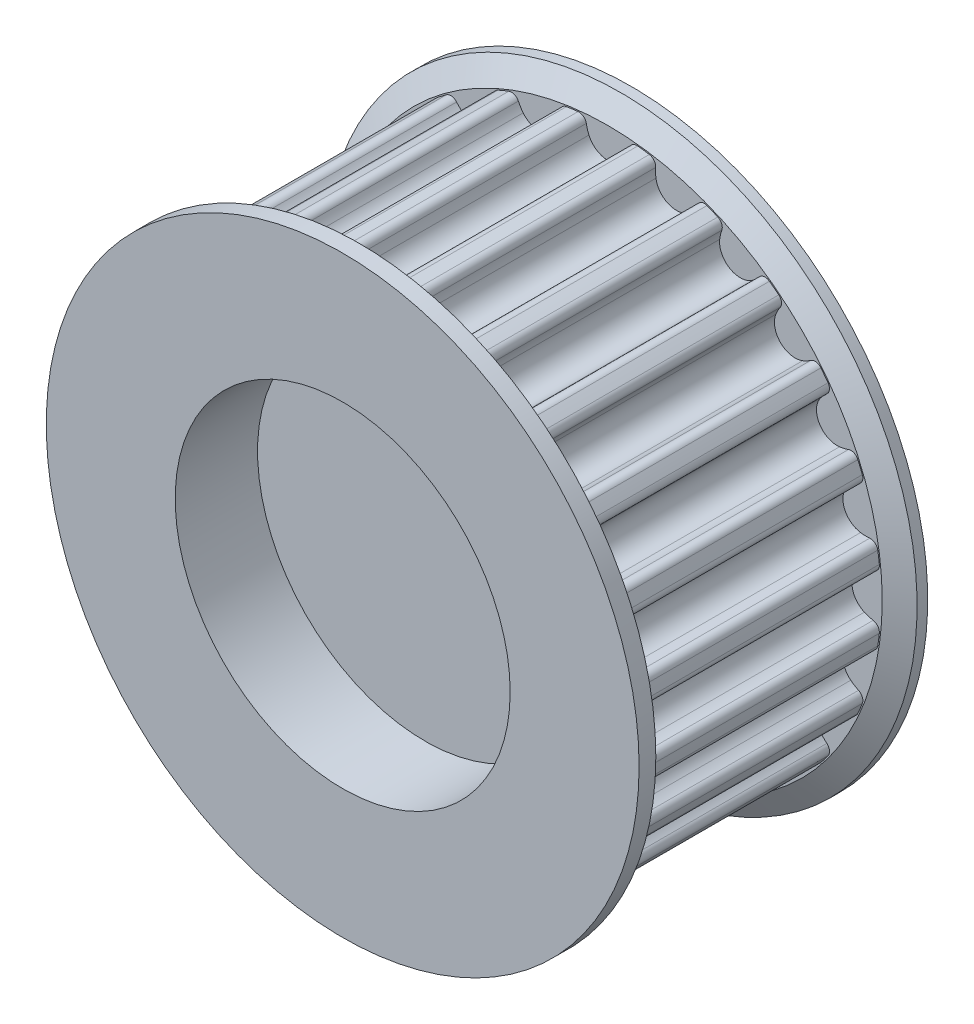
SolidWorks part; units mm, degrees
material "ABS"
ref_plane "Front" through (0, 0, 0) normal (0, 0, 1) x (1, 0, 0)
ref_plane "Top" through (0, 0, 0) normal (0, 1, 0) x (1, 0, 0)
ref_plane "Right" through (0, 0, 0) normal (1, 0, 0) x (0, 0, -1)
sketch "Sketch1" plane through (0, 0, 0) normal (0, 0, 1) x (1, 0, 0)
  arc A0 (-1.2885, 17.4069) -> (-1.4679, 18.0028) centre (1.1557, 18.4677) cw
  arc A1 (-1.4679, 18.0028) -> (-2.0236, 18.4192) centre (-1.9681, 17.9142) ccw
  arc A2 (-2.0236, 18.4192) -> (-2.8126, 18.3153) centre (0, 0) ccw
  arc A3 (-2.8126, 18.3153) -> (-3.2416, 17.7693) centre (-2.7355, 17.8132) ccw
  arc A4 (-3.2416, 17.7693) -> (-3.2606, 17.1473) centre (-5.8961, 17.5393) cw
  arc A5 (-3.2606, 17.1473) -> (-5.7499, 16.4803) centre (-4.65, 17.3539) cw
  arc A6 (-5.7499, 16.4803) -> (-6.0774, 17.0095) centre (-3.6635, 18.1375) cw
  arc A7 (-6.0774, 17.0095) -> (-6.7219, 17.2678) centre (-6.5376, 16.7944) ccw
  arc A8 (-6.7219, 17.2678) -> (-7.4571, 16.9633) centre (0, 0) ccw
  arc A9 (-7.4571, 16.9633) -> (-7.7302, 16.3249) centre (-7.2527, 16.4982) ccw
  arc A10 (-7.7302, 16.3249) -> (-7.5876, 15.7191) centre (-10.2347, 15.4156) cw
  arc A11 (-7.5876, 15.7191) -> (-9.8193, 14.4306) centre (-8.9831, 15.5591) cw
  arc A12 (-9.8193, 14.4306) -> (-10.2727, 14.857) centre (-8.233, 16.5713) cw
  arc A13 (-10.2727, 14.857) -> (-10.9621, 14.9397) centre (-10.6615, 14.5301) ccw
  arc A14 (-10.9621, 14.9397) -> (-11.5934, 14.4552) centre (0, 0) ccw
  arc A15 (-11.5934, 14.4552) -> (-11.692, 13.7679) centre (-11.2756, 14.0589) ccw
  arc A16 (-11.692, 13.7679) -> (-11.3974, 13.2197) centre (-13.8758, 12.2414) cw
  arc A17 (-11.3974, 13.2197) -> (-13.2197, 11.3974) centre (-12.704, 12.704) cw
  arc A18 (-13.2197, 11.3974) -> (-13.7679, 11.692) centre (-12.2414, 13.8758) cw
  arc A19 (-13.7679, 11.692) -> (-14.4552, 11.5934) centre (-14.0589, 11.2756) ccw
  arc A20 (-14.4552, 11.5934) -> (-14.9397, 10.9621) centre (0, 0) ccw
  arc A21 (-14.9397, 10.9621) -> (-14.857, 10.2727) centre (-14.5301, 10.6615) ccw
  arc A22 (-14.857, 10.2727) -> (-14.4306, 9.8193) centre (-16.5713, 8.233) cw
  arc A23 (-14.4306, 9.8193) -> (-15.7191, 7.5876) centre (-15.5591, 8.9831) cw
  arc A24 (-15.7191, 7.5876) -> (-16.3249, 7.7302) centre (-15.4156, 10.2347) cw
  arc A25 (-16.3249, 7.7302) -> (-16.9633, 7.4571) centre (-16.4982, 7.2527) ccw
  arc A26 (-16.9633, 7.4571) -> (-17.2678, 6.7219) centre (0, 0) ccw
  arc A27 (-17.2678, 6.7219) -> (-17.0095, 6.0774) centre (-16.7944, 6.5376) ccw
  arc A28 (-17.0095, 6.0774) -> (-16.4803, 5.7499) centre (-18.1375, 3.6635) cw
  arc A29 (-16.4803, 5.7499) -> (-17.1473, 3.2606) centre (-17.3539, 4.65) cw
  arc A30 (-17.1473, 3.2606) -> (-17.7693, 3.2416) centre (-17.5393, 5.8961) cw
  arc A31 (-17.7693, 3.2416) -> (-18.3153, 2.8126) centre (-17.8132, 2.7355) ccw
  arc A32 (-18.3153, 2.8126) -> (-18.4192, 2.0236) centre (0, 0) ccw
  arc A33 (-18.4192, 2.0236) -> (-18.0028, 1.4679) centre (-17.9142, 1.9681) ccw
  arc A34 (-18.0028, 1.4679) -> (-17.4069, 1.2885) centre (-18.4677, -1.1557) cw
  arc A35 (-17.4069, 1.2885) -> (-17.4069, -1.2885) centre (-17.9661, 0) cw
  arc A36 (-17.4069, -1.2885) -> (-18.0028, -1.4679) centre (-18.4677, 1.1557) cw
  arc A37 (-18.0028, -1.4679) -> (-18.4192, -2.0236) centre (-17.9142, -1.9681) ccw
  arc A38 (-18.4192, -2.0236) -> (-18.3153, -2.8126) centre (0, 0) ccw
  arc A39 (-18.3153, -2.8126) -> (-17.7693, -3.2416) centre (-17.8132, -2.7355) ccw
  arc A40 (-17.7693, -3.2416) -> (-17.1473, -3.2606) centre (-17.5393, -5.8961) cw
  arc A41 (-17.1473, -3.2606) -> (-16.4803, -5.7499) centre (-17.3539, -4.65) cw
  arc A42 (-16.4803, -5.7499) -> (-17.0095, -6.0774) centre (-18.1375, -3.6635) cw
  arc A43 (-17.0095, -6.0774) -> (-17.2678, -6.7219) centre (-16.7944, -6.5376) ccw
  arc A44 (-17.2678, -6.7219) -> (-16.9633, -7.4571) centre (0, 0) ccw
  arc A45 (-16.9633, -7.4571) -> (-16.3249, -7.7302) centre (-16.4982, -7.2527) ccw
  arc A46 (-16.3249, -7.7302) -> (-15.7191, -7.5876) centre (-15.4156, -10.2347) cw
  arc A47 (-15.7191, -7.5876) -> (-14.4306, -9.8193) centre (-15.5591, -8.9831) cw
  arc A48 (-14.4306, -9.8193) -> (-14.857, -10.2727) centre (-16.5713, -8.233) cw
  arc A49 (-14.857, -10.2727) -> (-14.9397, -10.9621) centre (-14.5301, -10.6615) ccw
  arc A50 (-14.9397, -10.9621) -> (-14.4552, -11.5934) centre (0, 0) ccw
  arc A51 (-14.4552, -11.5934) -> (-13.7679, -11.692) centre (-14.0589, -11.2756) ccw
  arc A52 (-13.7679, -11.692) -> (-13.2197, -11.3974) centre (-12.2414, -13.8758) cw
  arc A53 (-13.2197, -11.3974) -> (-11.3974, -13.2197) centre (-12.704, -12.704) cw
  arc A54 (-11.3974, -13.2197) -> (-11.692, -13.7679) centre (-13.8758, -12.2414) cw
  arc A55 (-11.692, -13.7679) -> (-11.5934, -14.4552) centre (-11.2756, -14.0589) ccw
  arc A56 (-11.5934, -14.4552) -> (-10.9621, -14.9397) centre (0, 0) ccw
  arc A57 (-10.9621, -14.9397) -> (-10.2727, -14.857) centre (-10.6615, -14.5301) ccw
  arc A58 (-10.2727, -14.857) -> (-9.8193, -14.4306) centre (-8.233, -16.5713) cw
  arc A59 (-9.8193, -14.4306) -> (-7.5876, -15.7191) centre (-8.9831, -15.5591) cw
  arc A60 (-7.5876, -15.7191) -> (-7.7302, -16.3249) centre (-10.2347, -15.4156) cw
  arc A61 (-7.7302, -16.3249) -> (-7.4571, -16.9633) centre (-7.2527, -16.4982) ccw
  arc A62 (-7.4571, -16.9633) -> (-6.7219, -17.2678) centre (0, 0) ccw
  arc A63 (-6.7219, -17.2678) -> (-6.0774, -17.0095) centre (-6.5376, -16.7944) ccw
  arc A64 (-6.0774, -17.0095) -> (-5.7499, -16.4803) centre (-3.6635, -18.1375) cw
  arc A65 (-5.7499, -16.4803) -> (-3.2606, -17.1473) centre (-4.65, -17.3539) cw
  arc A66 (-3.2606, -17.1473) -> (-3.2416, -17.7693) centre (-5.8961, -17.5393) cw
  arc A67 (-3.2416, -17.7693) -> (-2.8126, -18.3153) centre (-2.7355, -17.8132) ccw
  arc A68 (-2.8126, -18.3153) -> (-2.0236, -18.4192) centre (0, 0) ccw
  arc A69 (-2.0236, -18.4192) -> (-1.4679, -18.0028) centre (-1.9681, -17.9142) ccw
  arc A70 (-1.4679, -18.0028) -> (-1.2885, -17.4069) centre (1.1557, -18.4677) cw
  arc A71 (-1.2885, -17.4069) -> (1.2885, -17.4069) centre (0, -17.9661) cw
  arc A72 (1.2885, -17.4069) -> (1.4679, -18.0028) centre (-1.1557, -18.4677) cw
  arc A73 (1.4679, -18.0028) -> (2.0236, -18.4192) centre (1.9681, -17.9142) ccw
  arc A74 (2.0236, -18.4192) -> (2.8126, -18.3153) centre (0, 0) ccw
  arc A75 (2.8126, -18.3153) -> (3.2416, -17.7693) centre (2.7355, -17.8132) ccw
  arc A76 (3.2416, -17.7693) -> (3.2606, -17.1473) centre (5.8961, -17.5393) cw
  arc A77 (3.2606, -17.1473) -> (5.7499, -16.4803) centre (4.65, -17.3539) cw
  arc A78 (5.7499, -16.4803) -> (6.0774, -17.0095) centre (3.6635, -18.1375) cw
  arc A79 (6.0774, -17.0095) -> (6.7219, -17.2678) centre (6.5376, -16.7944) ccw
  arc A80 (6.7219, -17.2678) -> (7.4571, -16.9633) centre (0, 0) ccw
  arc A81 (7.4571, -16.9633) -> (7.7302, -16.3249) centre (7.2527, -16.4982) ccw
  arc A82 (7.7302, -16.3249) -> (7.5876, -15.7191) centre (10.2347, -15.4156) cw
  arc A83 (7.5876, -15.7191) -> (9.8193, -14.4306) centre (8.9831, -15.5591) cw
  arc A84 (9.8193, -14.4306) -> (10.2727, -14.857) centre (8.233, -16.5713) cw
  arc A85 (10.2727, -14.857) -> (10.9621, -14.9397) centre (10.6615, -14.5301) ccw
  arc A86 (10.9621, -14.9397) -> (11.5934, -14.4552) centre (0, 0) ccw
  arc A87 (11.5934, -14.4552) -> (11.692, -13.7679) centre (11.2756, -14.0589) ccw
  arc A88 (11.692, -13.7679) -> (11.3974, -13.2197) centre (13.8758, -12.2414) cw
  arc A89 (11.3974, -13.2197) -> (13.2197, -11.3974) centre (12.704, -12.704) cw
  arc A90 (13.2197, -11.3974) -> (13.7679, -11.692) centre (12.2414, -13.8758) cw
  arc A91 (13.7679, -11.692) -> (14.4552, -11.5934) centre (14.0589, -11.2756) ccw
  arc A92 (14.4552, -11.5934) -> (14.9397, -10.9621) centre (0, 0) ccw
  arc A93 (14.9397, -10.9621) -> (14.857, -10.2727) centre (14.5301, -10.6615) ccw
  arc A94 (14.857, -10.2727) -> (14.4306, -9.8193) centre (16.5713, -8.233) cw
  arc A95 (14.4306, -9.8193) -> (15.7191, -7.5876) centre (15.5591, -8.9831) cw
  arc A96 (15.7191, -7.5876) -> (16.3249, -7.7302) centre (15.4156, -10.2347) cw
  arc A97 (16.3249, -7.7302) -> (16.9633, -7.4571) centre (16.4982, -7.2527) ccw
  arc A98 (16.9633, -7.4571) -> (17.2678, -6.7219) centre (0, 0) ccw
  arc A99 (17.2678, -6.7219) -> (17.0095, -6.0774) centre (16.7944, -6.5376) ccw
  arc A100 (17.0095, -6.0774) -> (16.4803, -5.7499) centre (18.1375, -3.6635) cw
  arc A101 (16.4803, -5.7499) -> (17.1473, -3.2606) centre (17.3539, -4.65) cw
  arc A102 (17.1473, -3.2606) -> (17.7693, -3.2416) centre (17.5393, -5.8961) cw
  arc A103 (17.7693, -3.2416) -> (18.3153, -2.8126) centre (17.8132, -2.7355) ccw
  arc A104 (18.3153, -2.8126) -> (18.4192, -2.0236) centre (0, 0) ccw
  arc A105 (18.4192, -2.0236) -> (18.0028, -1.4679) centre (17.9142, -1.9681) ccw
  arc A106 (18.0028, -1.4679) -> (17.4069, -1.2885) centre (18.4677, 1.1557) cw
  arc A107 (17.4069, -1.2885) -> (17.4069, 1.2885) centre (17.9661, 0) cw
  arc A108 (17.4069, 1.2885) -> (18.0028, 1.4679) centre (18.4677, -1.1557) cw
  arc A109 (18.0028, 1.4679) -> (18.4192, 2.0236) centre (17.9142, 1.9681) ccw
  arc A110 (18.4192, 2.0236) -> (18.3153, 2.8126) centre (0, 0) ccw
  arc A111 (18.3153, 2.8126) -> (17.7693, 3.2416) centre (17.8132, 2.7355) ccw
  arc A112 (17.7693, 3.2416) -> (17.1473, 3.2606) centre (17.5393, 5.8961) cw
  arc A113 (17.1473, 3.2606) -> (16.4803, 5.7499) centre (17.3539, 4.65) cw
  arc A114 (16.4803, 5.7499) -> (17.0095, 6.0774) centre (18.1375, 3.6635) cw
  arc A115 (17.0095, 6.0774) -> (17.2678, 6.7219) centre (16.7944, 6.5376) ccw
  arc A116 (17.2678, 6.7219) -> (16.9633, 7.4571) centre (0, 0) ccw
  arc A117 (16.9633, 7.4571) -> (16.3249, 7.7302) centre (16.4982, 7.2527) ccw
  arc A118 (16.3249, 7.7302) -> (15.7191, 7.5876) centre (15.4156, 10.2347) cw
  arc A119 (15.7191, 7.5876) -> (14.4306, 9.8193) centre (15.5591, 8.9831) cw
  arc A120 (14.4306, 9.8193) -> (14.857, 10.2727) centre (16.5713, 8.233) cw
  arc A121 (14.857, 10.2727) -> (14.9397, 10.9621) centre (14.5301, 10.6615) ccw
  arc A122 (14.9397, 10.9621) -> (14.4552, 11.5934) centre (0, 0) ccw
  arc A123 (14.4552, 11.5934) -> (13.7679, 11.692) centre (14.0589, 11.2756) ccw
  arc A124 (13.7679, 11.692) -> (13.2197, 11.3974) centre (12.2414, 13.8758) cw
  arc A125 (13.2197, 11.3974) -> (11.3974, 13.2197) centre (12.704, 12.704) cw
  arc A126 (11.3974, 13.2197) -> (11.692, 13.7679) centre (13.8758, 12.2414) cw
  arc A127 (11.692, 13.7679) -> (11.5934, 14.4552) centre (11.2756, 14.0589) ccw
  arc A128 (11.5934, 14.4552) -> (10.9621, 14.9397) centre (0, 0) ccw
  arc A129 (10.9621, 14.9397) -> (10.2727, 14.857) centre (10.6615, 14.5301) ccw
  arc A130 (10.2727, 14.857) -> (9.8193, 14.4306) centre (8.233, 16.5713) cw
  arc A131 (9.8193, 14.4306) -> (7.5876, 15.7191) centre (8.9831, 15.5591) cw
  arc A132 (7.5876, 15.7191) -> (7.7302, 16.3249) centre (10.2347, 15.4156) cw
  arc A133 (7.7302, 16.3249) -> (7.4571, 16.9633) centre (7.2527, 16.4982) ccw
  arc A134 (7.4571, 16.9633) -> (6.7219, 17.2678) centre (0, 0) ccw
  arc A135 (6.7219, 17.2678) -> (6.0774, 17.0095) centre (6.5376, 16.7944) ccw
  arc A136 (6.0774, 17.0095) -> (5.7499, 16.4803) centre (3.6635, 18.1375) cw
  arc A137 (5.7499, 16.4803) -> (3.2606, 17.1473) centre (4.65, 17.3539) cw
  arc A138 (3.2606, 17.1473) -> (3.2416, 17.7693) centre (5.8961, 17.5393) cw
  arc A139 (3.2416, 17.7693) -> (2.8126, 18.3153) centre (2.7355, 17.8132) ccw
  arc A140 (2.8126, 18.3153) -> (2.0236, 18.4192) centre (0, 0) ccw
  arc A141 (2.0236, 18.4192) -> (1.4679, 18.0028) centre (1.9681, 17.9142) ccw
  arc A142 (1.4679, 18.0028) -> (1.2885, 17.4069) centre (-1.1557, 18.4677) cw
  arc A143 (1.2885, 17.4069) -> (-1.2885, 17.4069) centre (0, 17.9661) cw
extrude "Boss-Extrude1" add sketch "Sketch1" against normal blind 16
sketch "Sketch6" plane through (0, 0, -16) normal (0, 0, -1) x (-1, 0, 0)
  circle A0 centre (0, 0) radius 20.1175
  arc A1 (7.4571, 16.9633) -> (6.7219, 17.2678) centre (0, 0) ccw construction
  dimension "D1" = 1.5875
extrude "Boss-Extrude3" add sketch "Sketch6" along normal blind 1.5875
sketch "Sketch7" plane through (0, 0, 0) normal (0, 0, 1) x (1, 0, 0)
  circle A0 centre (0, 0) radius 20.1175
  circle A1 centre (0, 0) radius 20.1175 construction
extrude "Boss-Extrude4" add sketch "Sketch7" along normal blind 2
chamfer "Chamfer3" distance 1.5 angle 30 2 edges at (-20.1175, 0, -16) (20.1175, 0, 0)
sketch "Sketch8" plane through (0, 0, -17.5875) normal (0, 0, -1) x (-1, 0, 0)
  circle A0 centre (0, 0) radius 11.3665
  dimension "D1" = 22.733
extrude "Cut-Extrude4" cut sketch "Sketch8" against normal blind 5.588
sketch "Sketch9" plane through (0, 0, 2) normal (0, 0, 1) x (1, 0, 0)
  circle A0 centre (0, 0) radius 11.3665
  circle A1 centre (0, 0) radius 11.3665 construction
extrude "Cut-Extrude5" cut sketch "Sketch9" against normal blind 5.588
sketch "Sketch10" plane through (0, 0, -3.588) normal (0, 0, 1) x (1, 0, 0)
  circle A0 centre (0, 0) radius 9.525
  dimension "D1" = 19.05
extrude "Cut-Extrude6" cut sketch "Sketch10" against normal through all
sketch "Sketch11" plane through (0, 0, -3.588) normal (0, 0, 1) x (1, 0, 0)
  circle A0 centre (0, 0) radius 9.525
  circle A1 centre (0, 0) radius 9.525 construction
extrude "For Printing" add sketch "Sketch11" against normal blind 0.75
